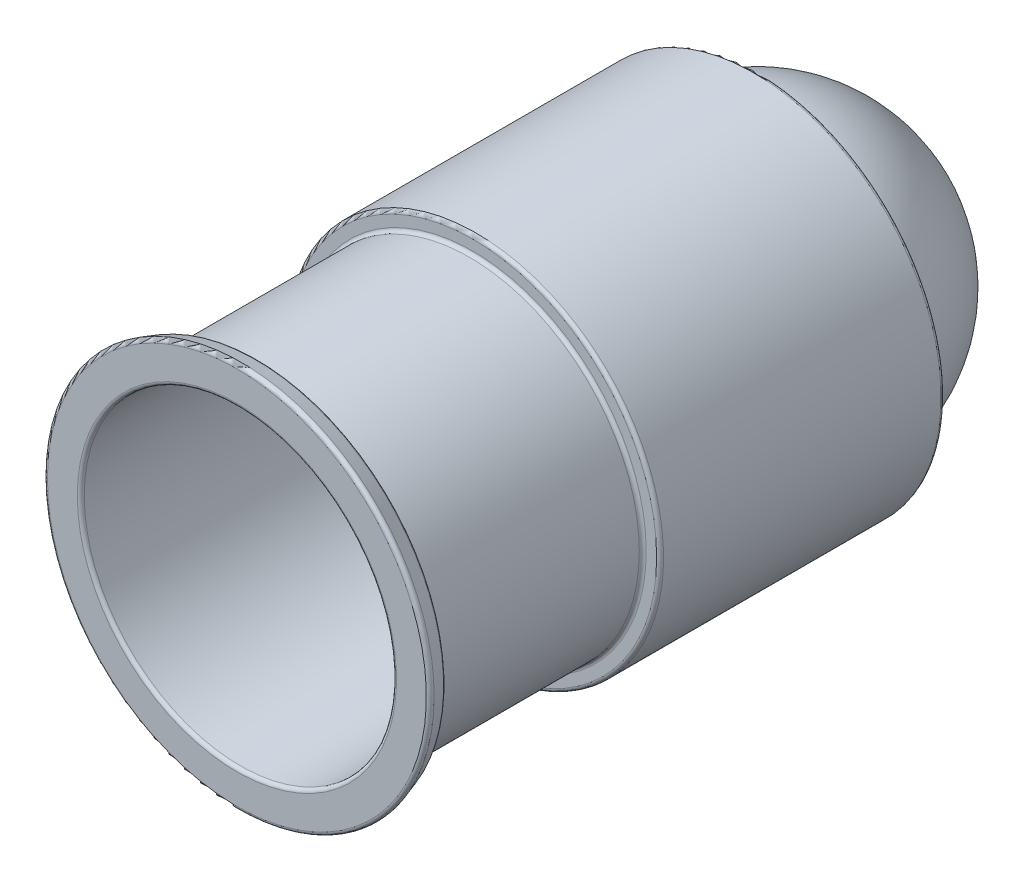
SolidWorks part; units mm, degrees
material "Acier inoxydable chromé"
ref_plane "Plan de face" through (0, 0, 0) normal (0, 0, 1) x (1, 0, 0)
ref_plane "Plan de dessus" through (0, 0, 0) normal (0, 1, 0) x (1, 0, 0)
ref_plane "Plan de droite" through (0, 0, 0) normal (1, 0, 0) x (0, 0, -1)
sketch "Esquisse1" plane through (0, 0, 0) normal (0, 1, 0) x (1, 0, 0)
  line L0 (4, 0) -> (-0.3063, 0)
  line L1 (5, 72.5) -> (6.5978, 72.5)
  line L2 (0.3604, 3) -> (2, 3)
  line L3 (2.5, 3.5) -> (2.5, 33.5)
  line L4 (2, 34) -> (0.5, 34)
  line L5 (0, 34.5) -> (0, 74.5)
  line L6 (0.5, 75) -> (4.0054, 75)
  line L7 (4.5, 72) -> (4.5, 0.5)
  line L8 (-0.114, 2.6581) -> (-0.7806, 0.6581)
  line L9 (15, 91.2481) -> (15, 93.1039)
  line L10 (27, 75) -> (27, -7.2922) construction
  arc A0 (14.2159, 93.5153) -> (4.5053, 75.4891) centre (27, 75) ccw
  arc A1 (14.8049, 90.8518) -> (7.0954, 73.0488) centre (27, 75) ccw
  arc A2 (4, 0) -> (4.5, 0.5) centre (4, 0.5) ccw
  arc A3 (2, 3) -> (2.5, 3.5) centre (2, 3.5) ccw
  arc A4 (-0.114, 2.6581) -> (0.3604, 3) centre (0.3604, 2.5) cw
  arc A5 (-0.7806, 0.6581) -> (-0.3063, 0) centre (-0.3063, 0.5) ccw
  arc A6 (0.5, 34) -> (0, 34.5) centre (0.5, 34.5) cw
  arc A7 (2.5, 33.5) -> (2, 34) centre (2, 33.5) ccw
  arc A8 (5, 72.5) -> (4.5, 72) centre (5, 72) ccw
  arc A9 (6.5978, 72.5) -> (7.0954, 73.0488) centre (6.5978, 73) ccw
  arc A10 (0, 74.5) -> (0.5, 75) centre (0.5, 74.5) cw
  arc A11 (4.0054, 75) -> (4.5053, 75.4891) centre (4.0054, 75.5) ccw
  arc A12 (15, 91.2481) -> (14.8049, 90.8518) centre (14.5, 91.2481) cw
  arc A13 (15, 93.1039) -> (14.2159, 93.5153) centre (14.5, 93.1039) ccw
  point P18 (2.5, 3)
  point P21 (0, 3)
  point P24 (-1, 0)
  point P31 (4.5, 72.5)
  point P38 (4.5, 75)
  dimension "D7" = 2.5
  dimension "D8" = 75
  dimension "D9" = 22.5
  dimension "D10" = 75
  dimension "D6" = 40
  dimension "D13" = 0.5
  dimension "D1" = 1
  dimension "D2" = 3
  dimension "D3" = 2.5
  dimension "D4" = 31
  dimension "D5" = 2
  dimension "D11" = 2.5
  dimension "D12" = 15
revolve "Révolution1" add sketch "Esquisse1" angle 360 about L10
